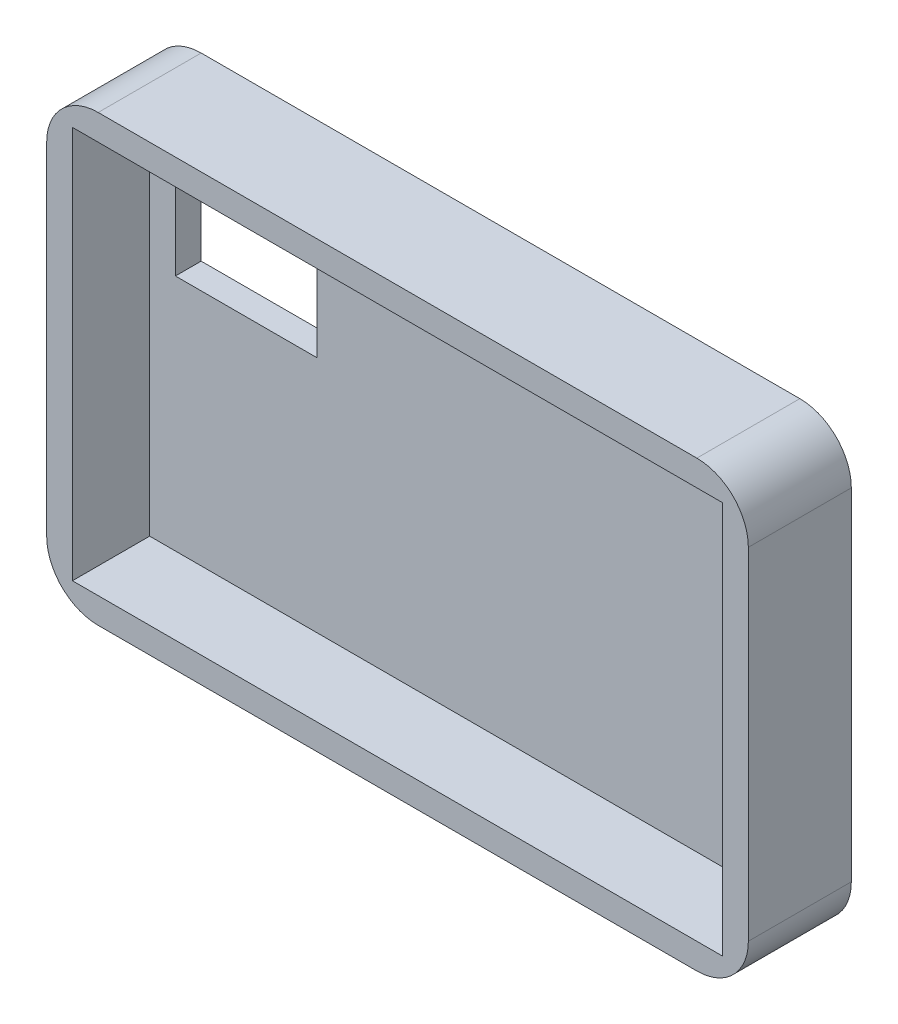
SolidWorks part; units mm, degrees
ref_plane "Front Plane" through (0, 0, 0) normal (0, 0, 1) x (1, 0, 0)
ref_plane "Top Plane" through (0, 0, 0) normal (0, 1, 0) x (1, 0, 0)
ref_plane "Right Plane" through (0, 0, 0) normal (1, 0, 0) x (0, 0, -1)
sketch "Sketch2" plane through (0, 0, 0) normal (0, 0, 1) x (1, 0, 0)
  line L1 (-27.25, 17.25) -> (27.25, 17.25)
  line L2 (-27.25, 17.25) -> (-27.25, -17.25)
  line L3 (-27.25, -17.25) -> (27.25, -17.25)
  line L4 (27.25, 17.25) -> (27.25, -17.25)
  line L5 (-27.25, 17.25) -> (27.25, -17.25) construction
  line L6 (-27.25, -17.25) -> (27.25, 17.25) construction
  point P0 (0, 0)
  dimension "D1" = 54.5
  dimension "D2" = 34.5
extrude "Boss-Extrude1" add sketch "Sketch2" along normal blind 8
shell "Shell1" thickness 2
fillet "Fillet2" radius 4 4 edges at (-27.25, -17.25, 4) (27.25, -17.25, 4) (27.25, 17.25, 4) (-27.25, 17.25, 4)
ref_plane "Plane1" through (0, 0, -10) normal (0, 0, -1) x (-1, 0, 0)
sketch "Sketch3" plane through (0, 0, -10) normal (0, 0, -1) x (-1, 0, 0)
  line L0 (-23.25, 17.25) -> (23.25, 17.25) construction
  line L1 (12.25, 14.25) -> (23.25, 14.25)
  line L2 (12.25, 14.25) -> (12.25, 3.25)
  line L3 (12.25, 3.25) -> (23.25, 3.25)
  line L4 (23.25, 14.25) -> (23.25, 3.25)
  line L5 (12.25, 14.25) -> (23.25, 3.25) construction
  line L6 (12.25, 3.25) -> (23.25, 14.25) construction
  line L7 (27.25, 13.25) -> (27.25, -13.25) construction
  point P0 (17.75, 8.75)
  point P5 (-17.7337, 8.1626)
  point P6 (16.0724, 8.2907)
  dimension "D1" = 11
  dimension "D2" = 11
  dimension "D3" = 3
  dimension "D4" = 4
extrude "Cut-Extrude1" cut sketch "Sketch3" against normal blind 26
